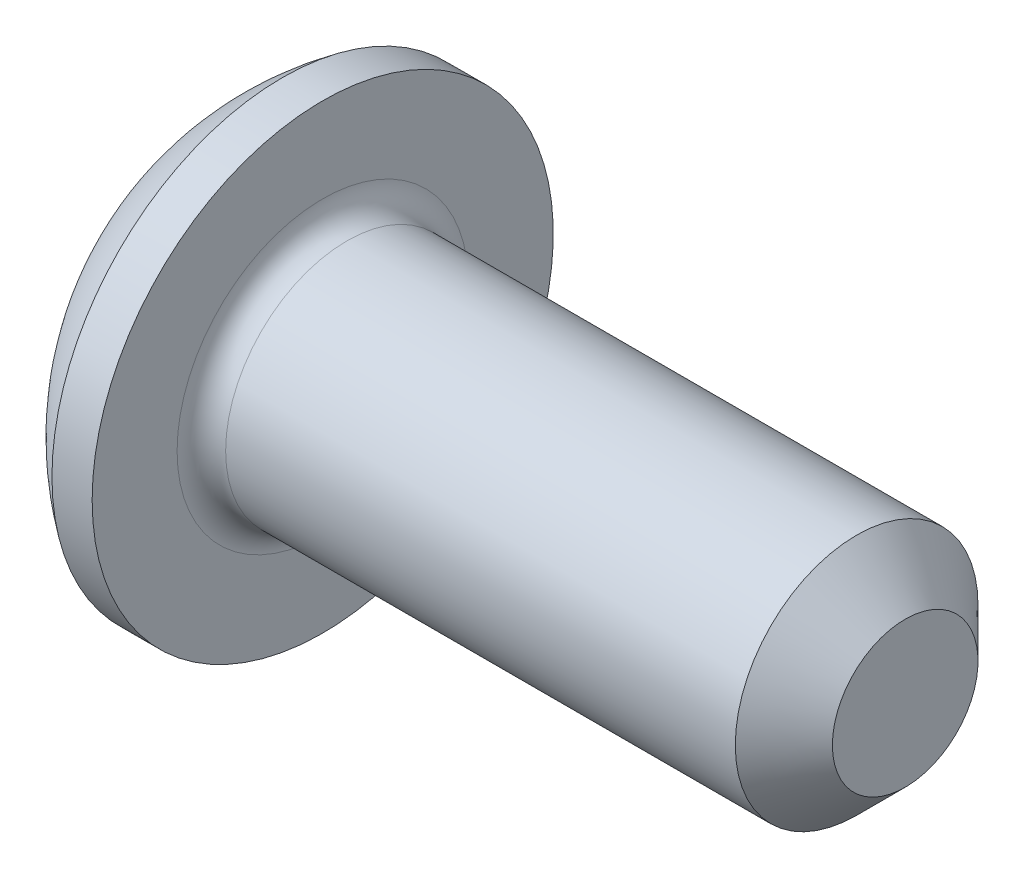
SolidWorks part; units mm, degrees
ref_plane "Спереди" through (0, 0, 0) normal (0, 0, 1) x (1, 0, 0)
ref_plane "Сверху" through (0, 0, 0) normal (0, 1, 0) x (1, 0, 0)
ref_plane "Справа" through (0, 0, 0) normal (1, 0, 0) x (0, 0, -1)
sketch "Эскиз1" plane through (0, 0, 0) normal (0, 0, 1) x (1, 0, 0)
  line L1 (0, 4.75) -> (0, 3)
  line L2 (-3.3, 0) -> (12, 0)
  line L3 (-6.6116, 0) -> (27.7012, 0) construction
  line L4 (0, 4.75) -> (-0.8283, 4.75)
  line L7 (0.5, 2.5) -> (11, 2.5)
  line L8 (12, 1.5) -> (12, 0)
  line L9 (11, 2.5) -> (12, 1.5)
  arc A0 (-0.8283, 4.75) -> (-3.3, 0) centre (2.5, 0) ccw
  arc A1 (0, 3) -> (0.5, 2.5) centre (0.5, 3) ccw
  point P12 (12, 2.5)
  dimension "D2" = 5.8
  dimension "D7" = 0.5
  dimension "D3" = 9.5
  dimension "D4" = 1
  dimension "D5" = 45
  dimension "D6" = 12
  dimension "D8" = 5
  dimension "D10" = 3.3
revolve "Основание-Повернуть" add sketch "Эскиз1" angle 360 about L3
cosmetic thread "Условное изображение резьбы1" parameters "D1"=11, "D2"=4
sketch "Эскиз2" plane through (0, 0, 0) normal (0, 0, 1) x (1, 0, 0)
  line L0 (-2.75, 2.4653) -> (-2.75, -2.4653)
  line L1 (0, -4.75) -> (0, 4.75) construction
  arc A0 (-0.8283, 4.75) -> (-0.8283, -4.75) centre (2.5, 0) ccw construction
  dimension "D1" = 2.75
extrude "Вырез-Вытянуть1" cut sketch "Эскиз2" against normal through all and the other way through all flip side to cut
sketch "Эскиз3" plane through (-2.75, 0, 0) normal (-1, 0, 0) x (0, 0, 1)
  line L1 (-1.7321, 0) -> (-0.866, -1.5)
  line L2 (-0.866, -1.5) -> (0.866, -1.5)
  line L3 (0.866, -1.5) -> (1.7321, 0)
  line L4 (1.7321, 0) -> (0.866, 1.5)
  line L5 (0.866, 1.5) -> (-0.866, 1.5)
  line L6 (-0.866, 1.5) -> (-1.7321, 0)
  circle A0 centre (0, 0) radius 1.5 construction
  dimension "D1" = 3
extrude "Вырез-Вытянуть2" cut sketch "Эскиз3" against normal blind 1.8
